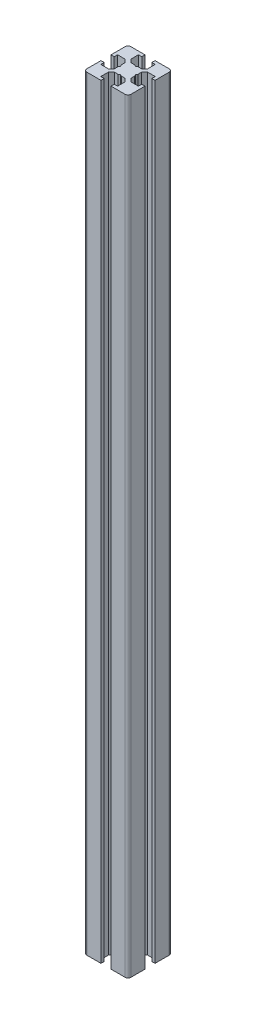
SolidWorks part; units mm, degrees
ref_plane "Front Plane" through (0, 0, 0) normal (0, 0, 1) x (1, 0, 0)
ref_plane "Top Plane" through (0, 0, 0) normal (0, 1, 0) x (1, 0, 0)
ref_plane "Right Plane" through (0, 0, 0) normal (1, 0, 0) x (0, 0, -1)
sketch "Sketch2" plane through (0, 0, 0) normal (0, 1, 0) x (1, 0, 0)
  line L3 (1.7, 7.5) -> (6.5, 7.5)
  line L5 (0, 2.5) -> (-0.5196, 2.8)
  line L6 (-2.85, 3.8) -> (-1.85, 2.8)
  line L9 (1.7, 6.4) -> (1.7, 7.5)
  line L10 (1.7, 6.4) -> (2.85, 6.4)
  line L11 (2.85, 6.4) -> (2.85, 3.8)
  line L12 (2.85, 3.8) -> (1.85, 2.8)
  line L13 (1.85, 2.8) -> (0.5196, 2.8)
  line L14 (2.8, -0.5196) -> (2.8, -1.85)
  line L15 (0, 2.5) -> (0.5196, 2.8)
  line L16 (-2.85, 6.4) -> (-2.85, 3.8)
  line L17 (-1.7, 6.4) -> (-2.85, 6.4)
  line L18 (-1.7, 6.4) -> (-1.7, 7.5)
  line L19 (-1.7, 7.5) -> (-6.5, 7.5)
  line L21 (7.5, -1.7) -> (7.5, -6.5)
  line L22 (6.4, -1.7) -> (7.5, -1.7)
  line L23 (6.4, -1.7) -> (6.4, -2.85)
  line L24 (6.4, -2.85) -> (3.8, -2.85)
  line L25 (2.5, 0) -> (2.8, 0.5196)
  line L26 (0.5196, -2.8) -> (1.85, -2.8)
  line L27 (2.8, 1.85) -> (2.8, 0.5196)
  line L28 (3.8, 2.85) -> (2.8, 1.85)
  line L29 (6.4, 2.85) -> (3.8, 2.85)
  line L30 (6.4, 1.7) -> (6.4, 2.85)
  line L31 (6.4, 1.7) -> (7.5, 1.7)
  line L32 (3.8, -2.85) -> (2.8, -1.85)
  line L33 (2.5, 0) -> (2.8, -0.5196)
  line L34 (7.5, 1.7) -> (7.5, 6.5)
  line L36 (-1.7, -6.4) -> (-1.7, -7.5)
  line L37 (0, -2.5) -> (0.5196, -2.8)
  line L38 (2.85, -3.8) -> (1.85, -2.8)
  line L39 (-1.85, -2.8) -> (-0.5196, -2.8)
  line L41 (0, -2.5) -> (-0.5196, -2.8)
  line L42 (2.85, -6.4) -> (2.85, -3.8)
  line L43 (1.7, -6.4) -> (2.85, -6.4)
  line L44 (1.7, -6.4) -> (1.7, -7.5)
  line L45 (1.7, -7.5) -> (6.5, -7.5)
  line L46 (-1.7, -7.5) -> (-6.5, -7.5)
  line L47 (-1.7, -6.4) -> (-2.85, -6.4)
  line L48 (-2.85, -6.4) -> (-2.85, -3.8)
  line L49 (-2.85, -3.8) -> (-1.85, -2.8)
  line L50 (-7.5, 1.7) -> (-7.5, 6.5)
  line L51 (-6.4, 1.7) -> (-7.5, 1.7)
  line L52 (-6.4, 1.7) -> (-6.4, 2.85)
  line L53 (-6.4, 2.85) -> (-3.8, 2.85)
  line L54 (-2.5, 0) -> (-2.8, -0.5196)
  line L55 (-0.5196, 2.8) -> (-1.85, 2.8)
  line L56 (-2.8, -1.85) -> (-2.8, -0.5196)
  line L57 (-3.8, -2.85) -> (-2.8, -1.85)
  line L58 (-6.4, -2.85) -> (-3.8, -2.85)
  line L59 (-6.4, -1.7) -> (-6.4, -2.85)
  line L60 (-6.4, -1.7) -> (-7.5, -1.7)
  line L61 (-3.8, 2.85) -> (-2.8, 1.85)
  line L62 (-2.5, 0) -> (-2.8, 0.5196)
  line L63 (-7.5, -1.7) -> (-7.5, -6.5)
  line L64 (-2.8, 0.5196) -> (-2.8, 1.85)
  arc A0 (7.5, 6.5) -> (6.5, 7.5) centre (6.5, 6.5) ccw
  arc A1 (-7.5, 6.5) -> (-6.5, 7.5) centre (-6.5, 6.5) cw
  arc A2 (6.5, -7.5) -> (7.5, -6.5) centre (6.5, -6.5) ccw
  arc A3 (-6.5, -7.5) -> (-7.5, -6.5) centre (-6.5, -6.5) cw
  dimension "D11" = 2
  dimension "D2" = 3.4
  dimension "D3" = 5.7
  dimension "D6" = 2.6
  dimension "D7" = 1
  dimension "D8" = 1
extrude "Boss-Extrude1" add sketch "Sketch2" along normal blind 260
